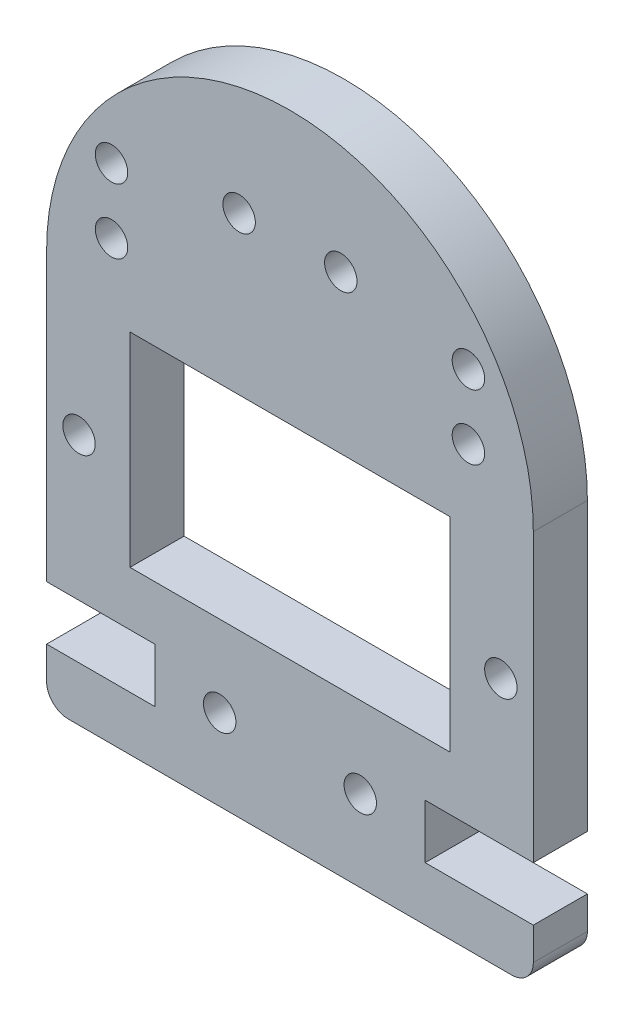
SolidWorks part; units mm, degrees
material "Acrílico (médio-alto impacto)"
ref_plane "Plano frontal" through (0, 0, 0) normal (0, 0, 1) x (1, 0, 0)
ref_plane "Plano superior" through (0, 0, 0) normal (0, 1, 0) x (1, 0, 0)
ref_plane "Plano direito" through (0, 0, 0) normal (1, 0, 0) x (0, 0, -1)
sketch "Esboço8" plane through (0, 0, 0) normal (0, 0, 1) x (1, 0, 0)
  line L0 (-24.2663, -3.25) -> (-24.2663, 13.25)
  line L1 (-14.2663, -13.25) -> (-14.2663, -18.25)
  line L2 (10.7337, -18.25) -> (20.7337, -18.25)
  line L3 (20.7337, -3.2223) -> (20.7337, 13.25)
  line L4 (-14.2663, -13.25) -> (-24.2663, -13.25)
  line L5 (-14.2663, -18.25) -> (-24.2663, -18.25)
  line L6 (20.7337, -3.25) -> (20.7337, -3.2223)
  line L7 (-24.2663, -18.25) -> (-24.2663, -21.25)
  line L9 (-24.2663, -13.25) -> (-24.2663, -3.25)
  line L10 (10.7337, -13.25) -> (20.7337, -13.25)
  line L11 (20.7337, -18.25) -> (20.7337, -21.25)
  line L12 (18.7337, -23.25) -> (-22.2663, -23.25)
  line L17 (10.7337, -13.25) -> (10.7337, -18.25)
  line L18 (20.7337, -13.25) -> (20.7337, -3.25)
  arc A0 (20.7337, 13.25) -> (-24.2663, 13.25) centre (-1.7663, 13.25) ccw
  arc A1 (-24.2663, -21.25) -> (-22.2663, -23.25) centre (-22.2663, -21.25) ccw
  arc A2 (18.7337, -23.25) -> (20.7337, -21.25) centre (18.7337, -21.25) ccw
  point P0 (0, 0)
  dimension "D1" = 2
extrude "Ressalto-extrusão2" add sketch "Esboço8" along normal blind 5
sketch "Esboço9" plane through (0, 0, 0) normal (0, 0, -1) x (-1, 0, 0)
  line L0 (-20.7337, -13.25) -> (-20.7337, 13.25) construction
  line L1 (16.5563, -8.25) -> (-13.0237, -8.25)
  line L2 (16.5563, -8.25) -> (16.5563, 10.6)
  line L3 (16.5563, 10.6) -> (-13.0237, 10.6)
  line L4 (-13.0237, -8.25) -> (-13.0237, 10.6)
  line L5 (24.2663, 13.25) -> (24.2663, -13.25) construction
  line L6 (-10.7337, -13.25) -> (-20.7337, -13.25) construction
  dimension "D1" = 7.71
  dimension "D2" = 7.71
  dimension "D3" = 5
extrude "Corte-extrusão1" cut sketch "Esboço9" against normal blind 5
sketch "Esboço10" plane through (0, 0, 0) normal (0, 0, -1) x (-1, 0, 0)
  line L0 (-10.7337, -13.25) -> (-20.7337, -13.25) construction
  line L1 (-20.7337, -13.25) -> (-20.7337, 13.25) construction
  line L2 (24.2663, 13.25) -> (24.2663, -13.25) construction
  line L3 (24.2663, -13.25) -> (14.2663, -13.25) construction
  circle A0 centre (-17.7337, 0) radius 1.5
  circle A1 centre (21.2663, 0) radius 1.5
  dimension "D1" = 13.25
  dimension "D2" = 3
  dimension "D3" = 3
  dimension "D4" = 13.25
extrude "Corte-extrusão2" cut sketch "Esboço10" against normal blind 5
sketch "Esboço12" plane through (0, 0, 5) normal (0, 0, 1) x (1, 0, 0)
  line L0 (10.7337, -18.25) -> (10.7337, -13.25) construction
  line L1 (-14.2663, -13.25) -> (-14.2663, -18.25) construction
  circle A0 centre (4.7337, -15.75) radius 1.5
  circle A1 centre (-8.2663, -15.75) radius 1.5
  dimension "D1" = 6
  dimension "D2" = 6
extrude "Corte-extrusão3" cut sketch "Esboço12" against normal blind 10
sketch "Esboço13" plane through (0, 0, 5) normal (0, 0, 1) x (1, 0, 0)
  line L2 (20.7337, -13.25) -> (20.7337, 13.25) construction
  circle A0 centre (2.9337, 25.15) radius 1.5
  arc A1 (20.7337, 13.25) -> (-24.2663, 13.25) centre (-1.7663, 13.25) ccw construction
  circle A2 centre (-6.4663, 25.15) radius 1.5
  point P5 (-1.7663, 35.75)
  dimension "D1" = 10.6
  dimension "D2" = 9.4
  dimension "D3" = 17.8
  dimension "D4" = 10.6
extrude "Corte-extrusão4" cut sketch "Esboço13" against normal blind 10
sketch "Esboço14" plane through (0, 0, 5) normal (0, 0, 1) x (1, 0, 0)
  line L0 (-24.2663, -13.25) -> (-14.2663, -13.25) construction
  line L2 (20.7337, -13.25) -> (20.7337, 13.25) construction
  line L3 (-16.5563, 10.6) -> (13.0237, 10.6) construction
  line L4 (-24.2663, 13.25) -> (-24.2663, -13.25) construction
  circle A0 centre (14.7337, 17.25) radius 1.5
  circle A1 centre (14.7337, 23.25) radius 1.5
  circle A2 centre (-18.2663, 23.25) radius 1.5
  circle A3 centre (-18.2663, 17.25) radius 1.5
  point P16 (-19.2663, -13.25)
  dimension "D1" = 6
  dimension "D2" = 6
  dimension "D3" = 6.65
  dimension "D4" = 6
  dimension "D5" = 6
  dimension "D6" = 6
  dimension "D7" = 30.5
extrude "Corte-extrusão5" cut sketch "Esboço14" against normal blind 76
